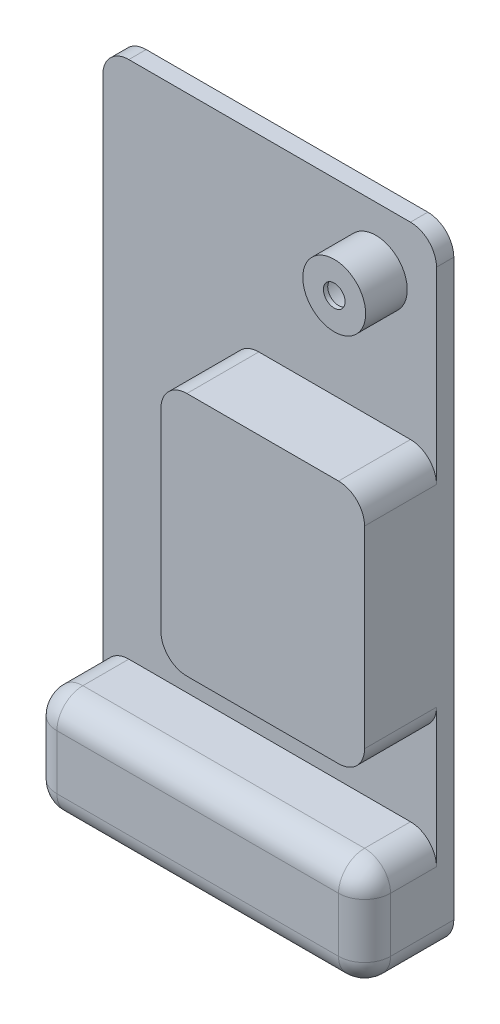
SolidWorks part; units mm, degrees
ref_plane "Ebene vorne" through (0, 0, 0) normal (1, 0, 0) x (0, 1, 0)
ref_plane "Ebene oben" through (0, 0, 0) normal (0, 0, 1) x (0, 1, 0)
ref_plane "Ebene rechts" through (0, 0, 0) normal (0, 1, 0) x (-1, 0, 0)
sketch "Skizze2" plane through (0, 0, 0) normal (0, 0, 1) x (0, 1, 0)
  line L1 (-72.22, -38.5) -> (72.22, -38.5)
  line L2 (-72.22, -38.5) -> (-72.22, 38.5)
  line L3 (-72.22, 38.5) -> (72.22, 38.5)
  line L4 (72.22, -38.5) -> (72.22, 38.5)
  line L5 (-72.22, -38.5) -> (72.22, 38.5) construction
  line L6 (-72.22, 38.5) -> (72.22, -38.5) construction
  point P0 (0, 0)
  dimension "D1" = 77
  dimension "D2" = 144.44
extrude "Aufsatz-Linear austragen1" add sketch "Skizze2" along normal blind 4
sketch "Skizze4" plane through (0, 0, 4) normal (0, 0, 1) x (1, 0, 0)
  line L0 (0, -72.22) -> (0, -61.42) construction
  line L1 (-38.5, -72.22) -> (38.5, -72.22) construction
  line L2 (0, -2.2) -> (0, 2.2) construction
  line L3 (38.5, -72.22) -> (-38.5, -72.22)
  line L4 (38.5, -72.22) -> (38.5, 72.22) construction
  line L6 (-38.5, 72.22) -> (-38.5, -72.22) construction
  line L9 (-38.5, -72.22) -> (-38.5, -47.62)
  line L10 (-38.5, -47.62) -> (38.5, -47.62)
  line L11 (38.5, -72.22) -> (38.5, -47.62)
  dimension "D2" = 24.6
extrude "Aufsatz-Linear austragen2" add sketch "Skizze4" along normal blind 16.6
fillet "Verrundung2" radius 6 4 edges at (-38.5, 72.22, 2) (38.5, 72.22, 2) (38.5, -72.22, 10.3) (-38.5, -72.22, 10.3)
sketch "Skizze5" plane through (0, 0, 4) normal (0, 0, 1) x (1, 0, 0)
  line L1 (38.5, -27.72) -> (-8.5, -27.72)
  line L2 (38.5, -27.72) -> (38.5, 28.78)
  line L3 (38.5, 28.78) -> (-8.5, 28.78)
  line L4 (-8.5, -27.72) -> (-8.5, 28.78)
  line L5 (38.5, -47.62) -> (38.5, 66.22) construction
  line L6 (-32.5, -72.22) -> (32.5, -72.22) construction
  dimension "D1" = 56.5
  dimension "D2" = 47
  dimension "D3" = 44.5
extrude "Aufsatz-Linear austragen3" add sketch "Skizze5" along normal blind 16.6
fillet "Verrundung4" radius 6 4 edges at (38.5, -27.72, 12.3) (-8.5, -27.72, 12.3) (-8.5, 28.78, 12.3) (38.5, 28.78, 12.3)
sketch "Skizze7" plane through (0, 0, 4) normal (0, 0, 1) x (1, 0, 0)
  circle A0 centre (24.5031, 58.3491) radius 7.25
  dimension "D1" = 14.5
extrude "Aufsatz-Linear austragen5" add sketch "Skizze7" along normal blind 9.6
fillet "Verrundung5" radius 6 1 edges at (0, -47.62, 20.6)
fillet "Verrundung7" radius 6 9 edges at (-38.5, -47.62, 9.3) (-38.5, -49.3774, 18.8426) (-38.5, -59.92, 20.6) (-36.7426, -70.4626, 20.6) (38.5, -47.62, 9.3) (38.5, -49.3774, 18.8426) (38.5, -59.92, 20.6) (36.7426, -70.4626, 20.6) (0, -72.22, 20.6)
shell "Wandung2" thickness 1
sketch "Skizze8" plane through (0, 0, 13.6) normal (0, 0, 1) x (1, 0, 0)
  circle A0 centre (24.5031, 58.3491) radius 2.5
  dimension "D1" = 5
extrude "Schnitt-Linear austragen1" cut sketch "Skizze8" against normal through all
